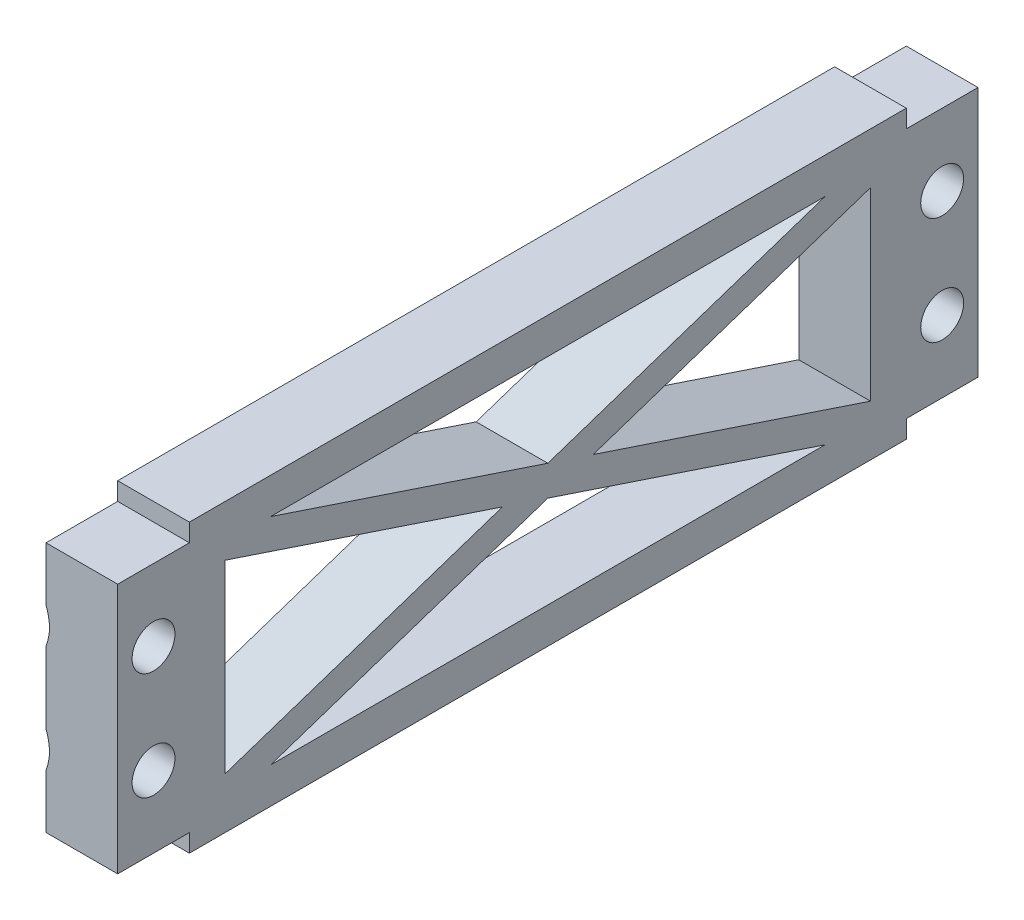
SolidWorks part; units mm, degrees
material "6061-T6 (SS)"
ref_plane "Front" through (0, 0, 0) normal (0, 0, 1) x (1, 0, 0)
ref_plane "Top" through (0, 0, 0) normal (0, 1, 0) x (1, 0, 0)
ref_plane "Right" through (0, 0, 0) normal (1, 0, 0) x (0, 0, -1)
sketch "Sketch1" plane through (0, 0, 0) normal (1, 0, 0) x (0, 0, -1)
  line L0 (38.1, 25.4) -> (38.1, 0) construction
  line L1 (0, 0) -> (76.2, 0)
  line L2 (0, 0) -> (0, 25.4)
  line L3 (0, 25.4) -> (76.2, 25.4)
  line L4 (76.2, 0) -> (76.2, 25.4)
  line L5 (76.2, 23.8125) -> (69.85, 23.8125)
  line L6 (76.2, 23.8125) -> (76.2, 1.5875)
  line L7 (76.2, 1.5875) -> (69.85, 1.5875)
  line L8 (69.85, 1.5875) -> (69.85, 0)
  line L9 (0, 1.5875) -> (6.35, 1.5875)
  line L10 (69.85, 23.8125) -> (69.85, 25.4)
  line L11 (0, 23.8125) -> (6.35, 23.8125)
  line L12 (6.35, 23.8125) -> (6.35, 25.4)
  line L13 (6.35, 1.5875) -> (6.35, 0)
  dimension "D1" = 25.4
  dimension "D2" = 76.2
  dimension "D3" = 6.35
  dimension "D4" = 1.5875
  dimension "D5" = 1.5875
extrude "Boss-Extrude1" add sketch "Sketch1" along normal blind 6.35 contours L3 L0 L1 L8 L7 L4 L5 L10 | L0 L3 L12 L11 L2 L9 L13 L1
hole_wizard "CSK for #6 Flat Head Machine Screw (100)1" positions "Sketch3" profile "Sketch2" countersink size "#6" standard "ANSI Inch" end condition through all
sketch "Sketch3" plane through (0, 0, 0) normal (-1, 0, 0) x (0, 0, 1)
  line L1 (-76.2, 23.8125) -> (-69.85, 23.8125) construction
  line L2 (0, 23.8125) -> (-6.35, 23.8125) construction
  line L3 (-6.35, 25.4) -> (-69.85, 25.4) construction
  point P0 (-73.025, 17.4625)
  point P2 (-73.025, 7.9375)
  point P4 (-3.175, 17.4625)
  point P6 (-3.175, 7.9375)
  point P13 (-73.025, 23.8125)
  point P16 (-3.175, 23.8125)
  dimension "D1" = 7.9375
  dimension "D2" = 7.9375
sketch "Sketch2" plane through (0, 17.4625, -73.025) normal (0, 1, 0) x (0, 0, 1)
  line L0 (0, 0) -> (0, 6.35)
  line L1 (0, 6.35) -> (1.8986, 6.35)
  line L2 (1.8986, 6.35) -> (1.8986, 1.38)
  line L3 (1.8986, 1.38) -> (3.5433, 0)
  line L5 (3.5433, 0) -> (0, 0)
  line L6 (-1.8986, 1.38) -> (-3.5433, 0) construction
  line L11 (0, -6.35) -> (0, 107.95) construction
  dimension "Thru Hole Dia." = 3.7973
  dimension "Thru Hole Depth" = 6.35
  dimension "Near C'Sink Dia." = 7.0866
  dimension "Near C'Sink Angle" = 100
sketch "Sketch4" plane through (0, 0, 0) normal (-1, 0, 0) x (0, 0, 1)
  line L0 (-6.35, 25.4) -> (-69.85, 25.4) construction
  line L1 (-66.675, 22.225) -> (-9.525, 22.225)
  line L2 (-66.675, 22.225) -> (-66.675, 3.175)
  line L3 (-66.675, 3.175) -> (-9.525, 3.175)
  line L4 (-9.525, 22.225) -> (-9.525, 3.175)
  line L5 (-66.675, 22.225) -> (-9.525, 3.175) construction
  line L6 (-66.675, 3.175) -> (-9.525, 22.225) construction
  line L7 (-6.35, 0) -> (-69.85, 0) construction
  line L8 (-67.0766, 21.0202) -> (-9.9266, 1.9702)
  line L9 (-66.2734, 1.9702) -> (-9.1234, 21.0202)
  line L10 (-66.2734, 23.4298) -> (-9.1234, 4.3798)
  line L11 (-67.0766, 4.3798) -> (-9.9266, 23.4298)
  arc A0 (-67.0766, 21.0202) -> (-66.2734, 23.4298) centre (-66.675, 22.225) cw
  arc A1 (-9.9266, 1.9702) -> (-9.1234, 4.3798) centre (-9.525, 3.175) ccw
  arc A2 (-66.2734, 1.9702) -> (-67.0766, 4.3798) centre (-66.675, 3.175) cw
  arc A3 (-9.1234, 21.0202) -> (-9.9266, 23.4298) centre (-9.525, 22.225) ccw
  point P0 (-38.1, 12.7)
  dimension "D1" = 3.175
  dimension "D2" = 3.175
  dimension "D3" = 3.175
  dimension "D4" = 3.175
  dimension "D5" = 1.27
  dimension "D6" = 1.27
extrude "Cut-Extrude1" cut sketch "Sketch4" against normal through all contours L2 L11 L8 | L10 L11 L1 | L9 L10 L4 | L9 L3 L8
